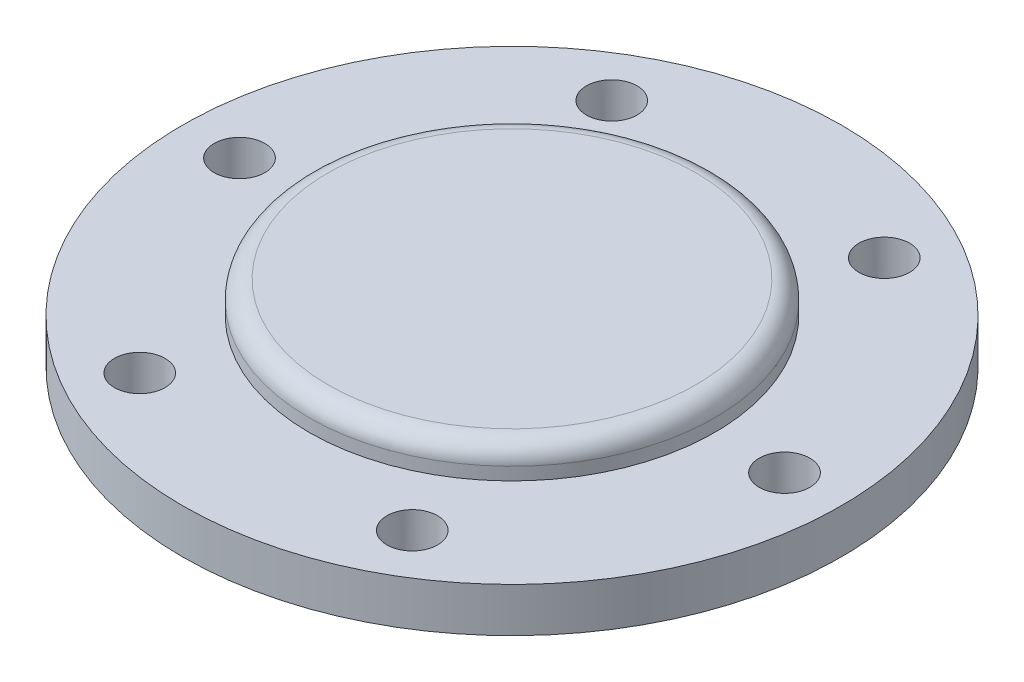
SolidWorks part; units mm, degrees
ref_plane "Front Plane" through (0, 0, 0) normal (0, 0, 1) x (1, 0, 0)
ref_plane "Top Plane" through (0, 0, 0) normal (0, 1, 0) x (1, 0, 0)
ref_plane "Right Plane" through (0, 0, 0) normal (1, 0, 0) x (0, 0, -1)
sketch "Sketch1" plane through (0, 0, 0) normal (0, 0, 1) x (1, 0, 0)
  line L1 (0, 3.5) -> (16, 3.5)
  line L2 (16, 3.5) -> (16, 1)
  line L3 (16, 1) -> (26, 1)
  line L4 (26, 1) -> (26, -2.5)
  line L5 (26, -2.5) -> (15, -2.5)
  line L6 (15, -2.5) -> (15, -3.5)
  line L7 (15, -3.5) -> (0, -3.5)
  line L8 (0, 3.5) -> (0, -3.5)
  point P3 (0, 0)
  point P4 (0, 0)
  dimension "D1" = 15
  dimension "D2" = 16
  dimension "D3" = 26
  dimension "D4" = 1
  dimension "D5" = 3.5
  dimension "D6" = 2.5
revolve "Revolve1" add sketch "Sketch1" angle 360 about L8
sketch "Sketch2" plane through (0, 0, 0) normal (0, 1, 0) x (1, 0, 0)
  circle A2 centre (-21.5, 0) radius 2
  circle A3 centre (-10.75, -18.6195) radius 2
  circle A4 centre (10.75, -18.6195) radius 2
  circle A5 centre (21.5, 0) radius 2
  circle A6 centre (10.75, 18.6195) radius 2
  circle A7 centre (-10.75, 18.6195) radius 2
  point P15 (0, 0)
  dimension "D1" = 6
  dimension "D2" = 4
  dimension "D3" = 10.75
extrude "Cut-Extrude1" cut sketch "Sketch2" against normal through all both and the other way through all
fillet "Fillet1" radius 1.5 1 edges at (0, 3.5, 16)
